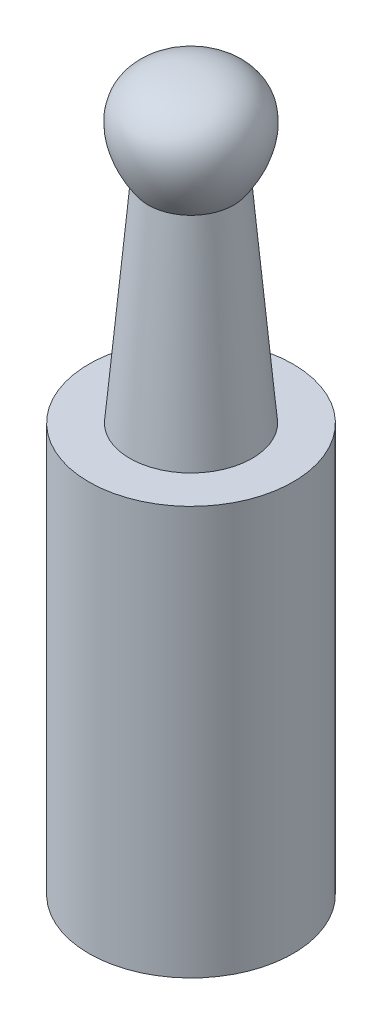
SolidWorks part; units mm, degrees
material "Brass"
ref_plane "Front Plane" through (0, 0, 0) normal (0, 0, 1) x (1, 0, 0)
ref_plane "Top Plane" through (0, 0, 0) normal (0, 1, 0) x (1, 0, 0)
ref_plane "Right Plane" through (0, 0, 0) normal (1, 0, 0) x (0, 0, -1)
sketch "Sketch1" plane through (0, 0, 0) normal (0, 1, 0) x (1, 0, 0)
  circle A0 centre (0, 0) radius 0.635
  dimension "D1" = 1.27
extrude "Boss-Extrude1" add sketch "Sketch1" along normal blind 2.54
sketch "Sketch3" plane through (0, 0, 0) normal (1, 0, 0) x (0, 0, -1)
  line L0 (-0.381, 2.54) -> (-0.2667, 3.847)
  line L1 (0.635, 2.54) -> (-0.635, 2.54) construction
  line L2 (0, 2.54) -> (-0.381, 2.54)
  line L3 (0, 2.54) -> (0, 4.445)
  spline S0 degree 3 poles (-0.2667, 3.847) (-0.3289, 3.9316) (-0.4612, 4.2446) (-0.281, 4.445) (0, 4.445) knots 0 0 0 0 0.311773 1 1 1 1
  dimension "D3" = 1.905
  dimension "D1" = 0.381
  dimension "D2" = 85
revolve "Revolve1" add sketch "Sketch3" angle 360 about L3
